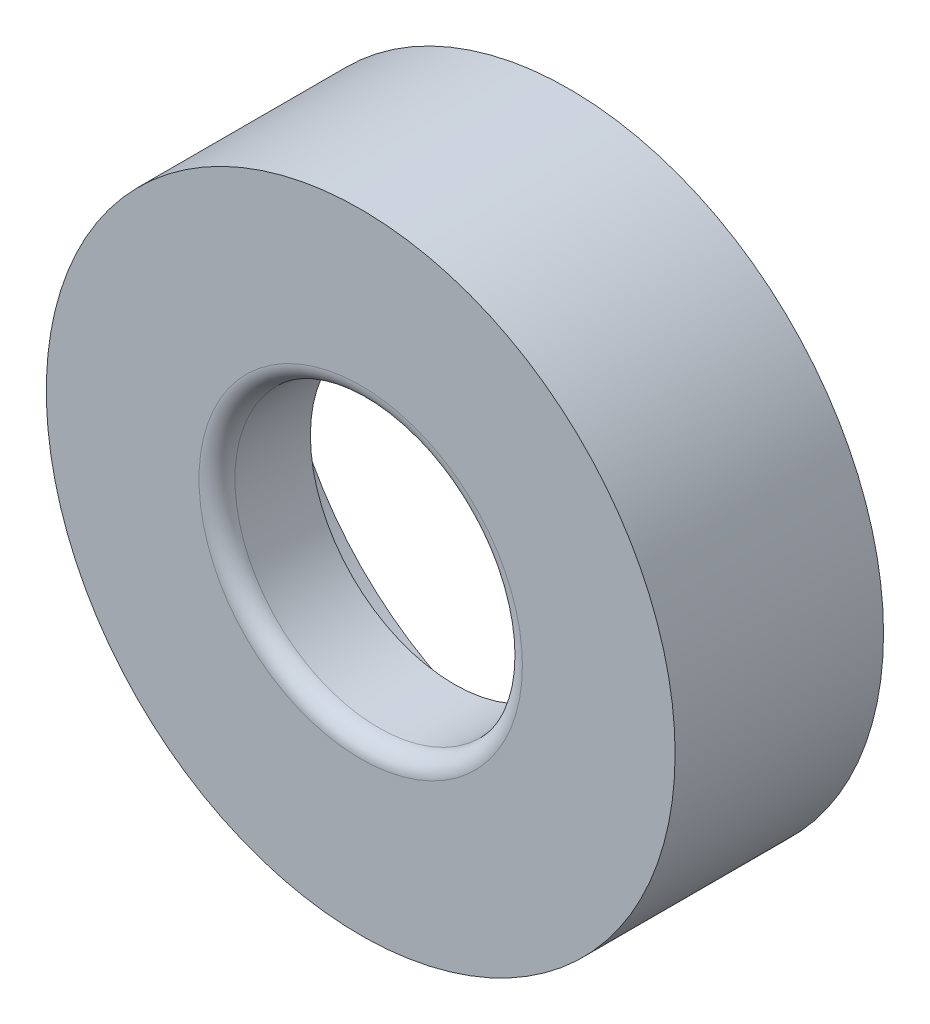
SolidWorks part; units mm, degrees
ref_plane "Front Plane" through (0, 0, 0) normal (0, 0, 1) x (1, 0, 0)
ref_plane "Top Plane" through (0, 0, 0) normal (0, 1, 0) x (1, 0, 0)
ref_plane "Right Plane" through (0, 0, 0) normal (1, 0, 0) x (0, 0, -1)
sketch "Sketch1" plane through (0, 0, 0) normal (0, 0, 1) x (1, 0, 0)
  circle A0 centre (85.2065, -1.764) radius 8.75
  dimension "D1" = 17.5
extrude "Boss-Extrude1" add sketch "Sketch1" along normal blind 5.8
sketch "Sketch2" plane through (0, 0, 5.8) normal (0, 0, 1) x (1, 0, 0)
  circle A0 centre (85.2065, -1.764) radius 4
  dimension "D1" = 8
extrude "Cut-Extrude1" cut sketch "Sketch2" against normal through all
sketch "Sketch3" plane through (0, 0, 0) normal (0, 0, -1) x (-1, 0, 0)
  circle A0 centre (-85.2065, -1.764) radius 8.1
  dimension "D1" = 16.2
extrude "Cut-Extrude2" cut sketch "Sketch3" against normal blind 3.2
fillet "Fillet1" radius 0.5 1 edges at (89.2065, -1.764, 5.8)
